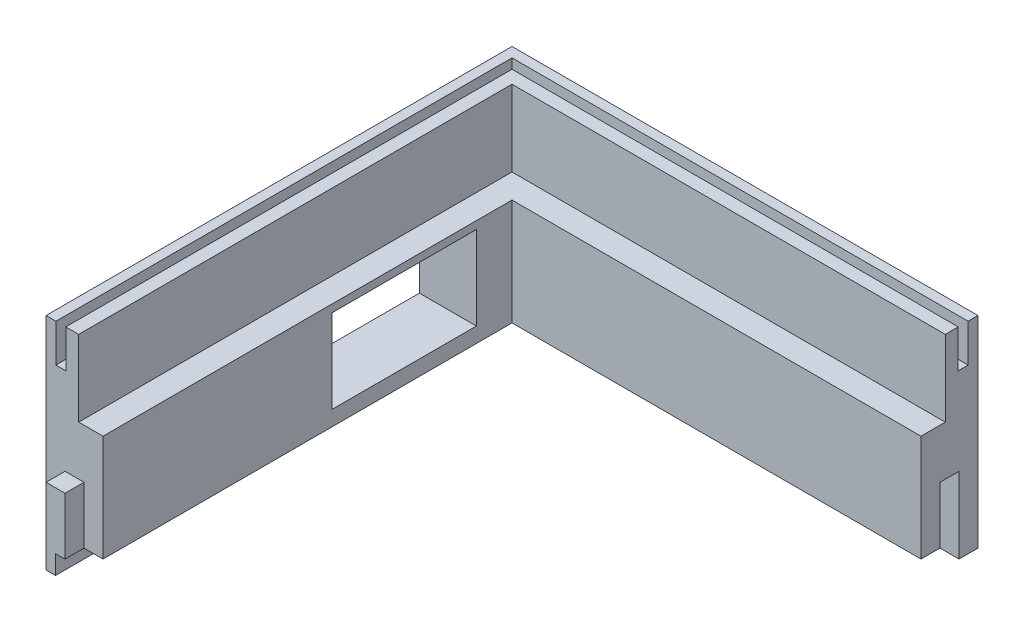
SolidWorks part; units mm, degrees
ref_plane "Front Plane" through (0, 0, 0) normal (0, 0, 1) x (1, 0, 0)
ref_plane "Top Plane" through (0, 0, 0) normal (0, 1, 0) x (1, 0, 0)
ref_plane "Right Plane" through (0, 0, 0) normal (1, 0, 0) x (0, 0, -1)
sketch "Sketch1" plane through (0, 0, 0) normal (0, 1, 0) x (1, 0, 0)
  line L7 (-60.6056, 37.6635) -> (95.0964, 37.6635)
  line L12 (95.0964, 37.6635) -> (95.0964, 18.6135)
  line L13 (95.0964, 18.6135) -> (-41.5556, 18.6135)
  line L14 (-41.5556, 18.6135) -> (-41.5556, -118.0385)
  line L15 (-41.5556, -118.0385) -> (-60.6056, -118.0385)
  line L16 (-60.6056, -118.0385) -> (-60.6056, 37.6635)
  line L17 (-57.3036, -118.0385) -> (-57.3036, 34.3615)
  line L18 (-57.3036, 34.3615) -> (95.0964, 34.3615)
  line L19 (-54.0016, -118.0385) -> (-54.0016, 31.0595)
  line L20 (-54.0016, 31.0595) -> (95.0964, 31.0595)
  line L21 (95.0964, 27.7575) -> (-50.6996, 27.7575)
  line L22 (-50.6996, 27.7575) -> (-50.6996, -118.0385)
  dimension "D1" = 155.702
  dimension "D2" = 19.05
  dimension "D3" = 3.302
  dimension "D4" = 3.302
  dimension "D5" = 3.302
extrude "Boss-Extrude5" add sketch "Sketch1" along normal blind 67.31 contours L14 L15 L16 L7 L12 L13
sketch "Sketch8" plane through (0, 67.31, 0) normal (0, 1, 0) x (1, 0, 0)
  line L0 (-57.3036, -118.0385) -> (-57.3036, 34.3615)
  line L1 (-57.3036, -118.0385) -> (-54.0016, -118.0385)
  line L2 (95.0964, 34.3615) -> (95.0964, 31.0595)
  line L3 (-41.5556, -118.0385) -> (-60.6056, -118.0385) construction
  line L4 (-57.3036, 34.3615) -> (95.0964, 34.3615)
  line L5 (95.0964, 37.6635) -> (95.0964, 18.6135) construction
  line L6 (-60.6056, -118.0385) -> (-60.6056, 37.6635) construction
  line L7 (-54.0016, -118.0385) -> (-54.0016, 31.0595)
  line L8 (-54.0016, 31.0595) -> (95.0964, 31.0595)
  dimension "D1" = 3.302
  dimension "D2" = 3.302
extrude "Cut-Extrude2" cut sketch "Sketch8" against normal blind 12.6933
sketch "Sketch9" plane through (0, 67.31, 0) normal (0, 1, 0) x (1, 0, 0)
  line L0 (-49.6836, -118.0385) -> (-49.6836, 26.7415)
  line L1 (-41.5556, -118.0385) -> (-54.0016, -118.0385) construction
  line L2 (-49.6836, 26.7415) -> (95.0964, 26.7415)
  line L3 (95.0964, 31.0595) -> (95.0964, 18.6135) construction
  line L4 (95.0964, 26.7415) -> (95.0964, 18.6135)
  line L5 (95.0964, 18.6135) -> (-41.5556, 18.6135)
  line L6 (-41.5556, 18.6135) -> (-41.5556, -118.0385)
  line L7 (-41.5556, -118.0385) -> (-49.6836, -118.0385)
  dimension "D1" = 4.318
extrude "Cut-Extrude3" cut sketch "Sketch9" against normal blind 25.4
sketch "Sketch11" plane through (0, 0, 118.0385) normal (0, 0, 1) x (1, 0, 0)
  line L0 (-41.5556, 0) -> (-60.6056, 0) construction
  line L1 (-54.2556, 0) -> (-47.9056, 0)
  line L2 (-54.2556, 0) -> (-54.2556, 25.4)
  line L3 (-54.2556, 25.4) -> (-47.9056, 25.4)
  line L4 (-47.9056, 0) -> (-47.9056, 25.4)
  dimension "D1" = 6.35
  dimension "D2" = 6.35
  dimension "D3" = 25.4
extrude "Boss-Extrude6" add sketch "Sketch11" along normal blind 6.35
sketch "Sketch12" plane through (95.0964, 0, 0) normal (1, 0, 0) x (0, 0, -1)
  line L0 (37.6635, 0) -> (18.6135, 0) construction
  line L1 (24.9635, 0) -> (31.3135, 0)
  line L2 (24.9635, 0) -> (24.9635, 25.4)
  line L3 (24.9635, 25.4) -> (31.3135, 25.4)
  line L4 (31.3135, 0) -> (31.3135, 25.4)
  dimension "D1" = 6.35
  dimension "D2" = 6.35
  dimension "D3" = 25.4
extrude "Cut-Extrude4" cut sketch "Sketch12" against normal blind 6.35
sketch "Sketch13" plane through (0, 0, 0) normal (0, -1, 0) x (1, 0, 0)
  line L4 (-51.0806, 124.3885) -> (-51.0806, -25.3997)
  line L5 (-54.2556, 124.3885) -> (-47.9056, 124.3885) construction
  line L6 (88.7464, -28.1385) -> (-51.0806, -28.1385)
  line L7 (88.7464, -24.9635) -> (88.7464, -31.3135) construction
  line L8 (-51.0806, -28.1385) -> (-51.0806, -25.3997)
extrude "Cut-Extrude5" cut sketch "Sketch13" against normal blind 6.35 and the other way through all
ref_plane "Plane1" through (-60.6056, 67.31, 118.0385) normal (0, -1, 0) x (-1, 0, 0)
sketch "Sketch15" plane through (-41.5556, 0, 0) normal (1, 0, 0) x (0, 0, -1)
  line L1 (-41.5425, 39.3498) -> (6.7175, 39.3498)
  line L2 (-41.5425, 39.3498) -> (-41.5425, 11.4098)
  line L3 (-41.5425, 11.4098) -> (6.7175, 11.4098)
  line L4 (6.7175, 39.3498) -> (6.7175, 11.4098)
  dimension "D1" = 48.26
  dimension "D2" = 27.94
extrude "Cut-Extrude6" cut sketch "Sketch15" against normal blind 45.212
